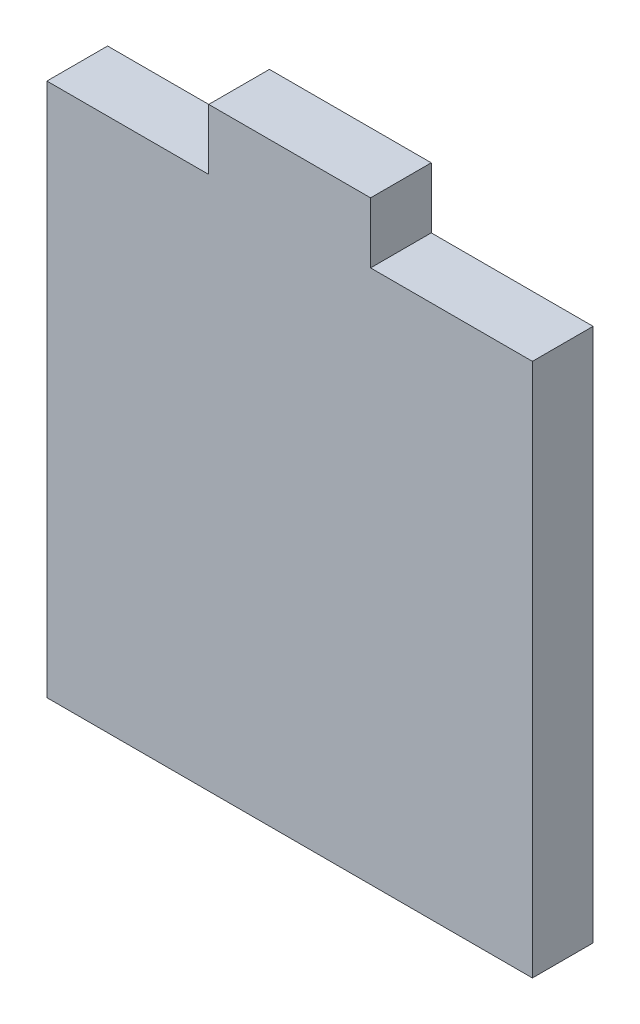
SolidWorks part; units mm, degrees
ref_plane "Front" through (0, 0, 0) normal (0, 0, 1) x (1, 0, 0)
ref_plane "Top" through (0, 0, 0) normal (0, 1, 0) x (1, 0, 0)
ref_plane "Right" through (0, 0, 0) normal (1, 0, 0) x (0, 0, -1)
sketch "Sketch1" plane through (0, 0, 0) normal (0, 0, 1) x (1, 0, 0)
  line L0 (25.4, 41.91) -> (38.1, 41.91)
  line L1 (0, 0) -> (38.1, 0)
  line L2 (0, 0) -> (0, 41.91)
  line L3 (0, 41.91) -> (12.7, 41.91)
  line L4 (38.1, 0) -> (38.1, 41.91)
  line L6 (12.7, 41.91) -> (12.7, 46.6725)
  line L7 (12.7, 46.6725) -> (25.4, 46.6725)
  line L8 (25.4, 41.91) -> (25.4, 46.6725)
  point P9 (12.7, 44.2912)
  dimension "D1" = 41.91
  dimension "D2" = 38.1
  dimension "D3" = 4.7625
  dimension "D4" = 12.7
  dimension "D5" = 12.7
extrude "Boss-Extrude1" add sketch "Sketch1" along normal blind 4.7625
